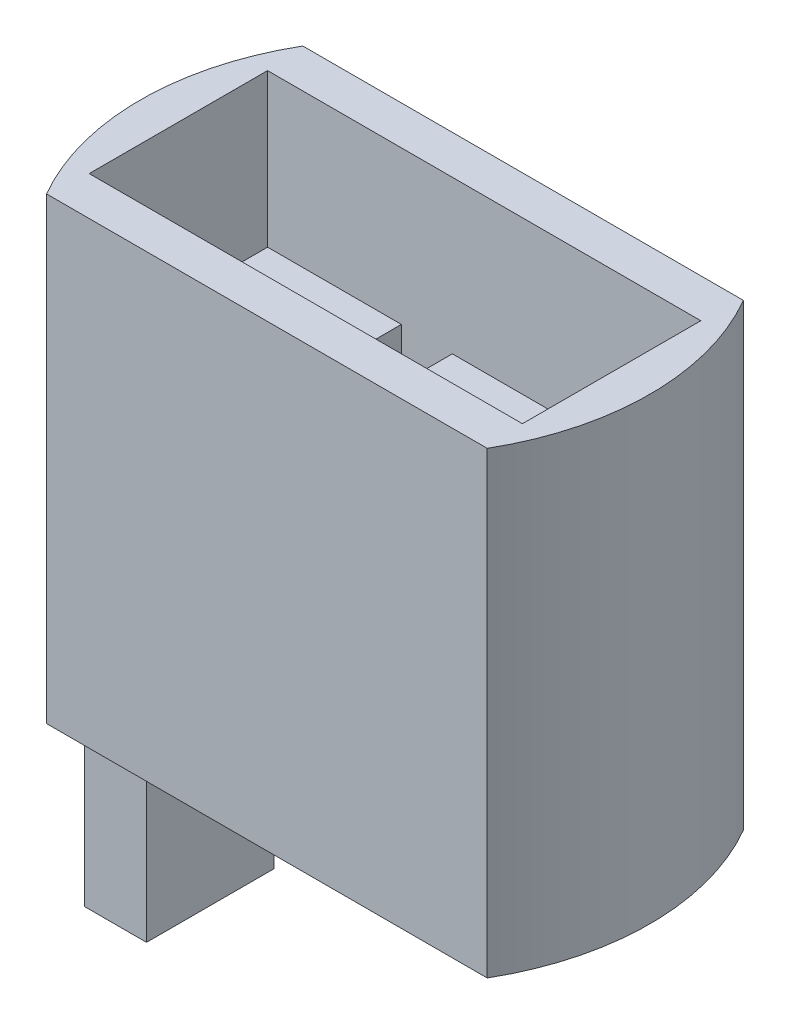
SolidWorks part; units mm, degrees
ref_plane "Front Plane" through (0, 0, 0) normal (0, 0, 1) x (1, 0, 0)
ref_plane "Top Plane" through (0, 0, 0) normal (0, 1, 0) x (1, 0, 0)
ref_plane "Right Plane" through (0, 0, 0) normal (1, 0, 0) x (0, 0, -1)
sketch "Sketch1" plane through (0, 0, 0) normal (0, 1, 0) x (1, 0, 0)
  circle A0 centre (0, 0) radius 10
  dimension "D1" = 20
extrude "Boss-Extrude1" add sketch "Sketch1" along normal blind 18
sketch "Sketch2" plane through (0, 0, 0) normal (0, -1, 0) x (-1, 0, 0)
  line L1 (8.05, 2.5) -> (7.25, 2.5)
  line L2 (8.05, 2.5) -> (8.05, -2.5)
  line L3 (8.05, -2.5) -> (7.25, -2.5)
  line L4 (7.25, 2.5) -> (7.25, -2.5)
  point P4 (7.25, 0)
  dimension "D1" = 5
  dimension "D2" = 0.8
  dimension "D3" = 7.25
extrude "Boss-Extrude2" add sketch "Sketch2" along normal blind 8 separate body
sketch "Sketch3" plane through (-8.05, 0, 0) normal (-1, 0, 0) x (0, 0, 1)
  line L0 (-2.5, -8) -> (-2.5, 0)
  line L1 (-2.5, 0) -> (2.5, 0)
  line L2 (2.5, 0) -> (2.5, -8)
  line L3 (2.5, -8) -> (1.5, -8)
  line L4 (2.5, -8) -> (-2.5, -8) construction
  line L5 (1.5, -8) -> (1.5, -0.75)
  line L6 (1.5, -0.75) -> (-1.5, -0.75)
  line L7 (-1.5, -0.75) -> (-1.5, -8)
  line L8 (-1.5, -8) -> (-2.5, -8)
  dimension "D1" = 1
  dimension "D2" = 1
  dimension "D3" = 0.75
extrude "Boss-Extrude3" add sketch "Sketch3" along normal blind 1.2
sketch "Sketch4" plane through (0, 18, 0) normal (0, 1, 0) x (1, 0, 0)
  line L0 (-10, 0) -> (10, 0) construction
  line L1 (-8.5, -3.5) -> (8.5, -3.5)
  line L2 (-8.5, -3.5) -> (-8.5, 3.5)
  line L3 (-8.5, 3.5) -> (8.5, 3.5)
  line L4 (8.5, -3.5) -> (8.5, 3.5)
  circle A0 centre (0, 0) radius 10 construction
  point P9 (-8.5, 0)
  dimension "D1" = 7
  dimension "D2" = 17
  dimension "D3" = 1.5
extrude "Cut-Extrude1" cut sketch "Sketch4" against normal blind 6
sketch "Sketch5" plane through (0, 12, 0) normal (0, 1, 0) x (1, 0, 0)
  line L0 (8.5, 0) -> (-1.25, 0) construction
  line L1 (8.5, -3.5) -> (8.5, 3.5) construction
  line L2 (8.5, 3.5) -> (-8.5, 3.5) construction
  line L3 (-1.25, 3.5) -> (-3.25, 3.5)
  line L4 (-1.25, 3.5) -> (-1.25, -3.5)
  line L5 (-1.25, -3.5) -> (-3.25, -3.5)
  line L6 (-3.25, 3.5) -> (-3.25, -3.5)
  line L7 (-8.5, -3.5) -> (8.5, -3.5) construction
  dimension "D1" = 9.75
  dimension "D2" = 2
extrude "Cut-Extrude2" cut sketch "Sketch5" against normal blind 4
sketch "Sketch6" plane through (0, 0, 0) normal (0, -1, 0) x (1, 0, 0)
  line L0 (-8.6446, 5.027) -> (8.6446, 5.027)
  line L1 (0, 0) -> (10, 0) construction
  line L2 (10, 0) -> (-10, 0) construction
  line L3 (-8.6446, -5.027) -> (8.6446, -5.027)
  arc A0 (-8.6446, 5.027) -> (8.6446, 5.027) centre (0, 0) cw
  circle A1 centre (0, 0) radius 10 construction
  circle A2 centre (0, 0) radius 10 construction
  arc A3 (-8.6446, -5.027) -> (8.6446, -5.027) centre (0, 0) ccw
  dimension "D1" = 8.6446
extrude "Cut-Extrude3" cut sketch "Sketch6" against normal blind 25
sketch "Sketch7" plane through (-9.25, 0, 0) normal (-1, 0, 0) x (0, 0, 1)
  line L1 (-2.5, -8) -> (2.5, -8)
  line L2 (-2.5, -8) -> (-2.5, 0)
  line L3 (-2.5, 0) -> (2.5, 0)
  line L4 (2.5, -8) -> (2.5, 0)
extrude "Boss-Extrude4" add sketch "Sketch7" along normal blind 0.8
sketch "Sketch8" plane through (0, 0, 0) normal (0, 1, 0) x (1, 0, 0)
  line L0 (-9.6825, 2.5) -> (-10.05, 2.5)
  line L1 (-10.05, 2.5) -> (-10.05, -2.5)
  line L2 (-10.05, -2.5) -> (-10.05, 2.5) construction
  line L3 (-10.05, -2.5) -> (-9.6825, -2.5)
  line L4 (-9.6825, -2.5) -> (-10.05, -2.5) construction
  arc A0 (-9.6825, 2.5) -> (-9.6825, -2.5) centre (0, 0) ccw construction
  arc A1 (-9.6825, 2.5) -> (-9.6825, -2.5) centre (0, 0) ccw
extrude "Cut-Extrude4" cut sketch "Sketch8" against normal up to next
